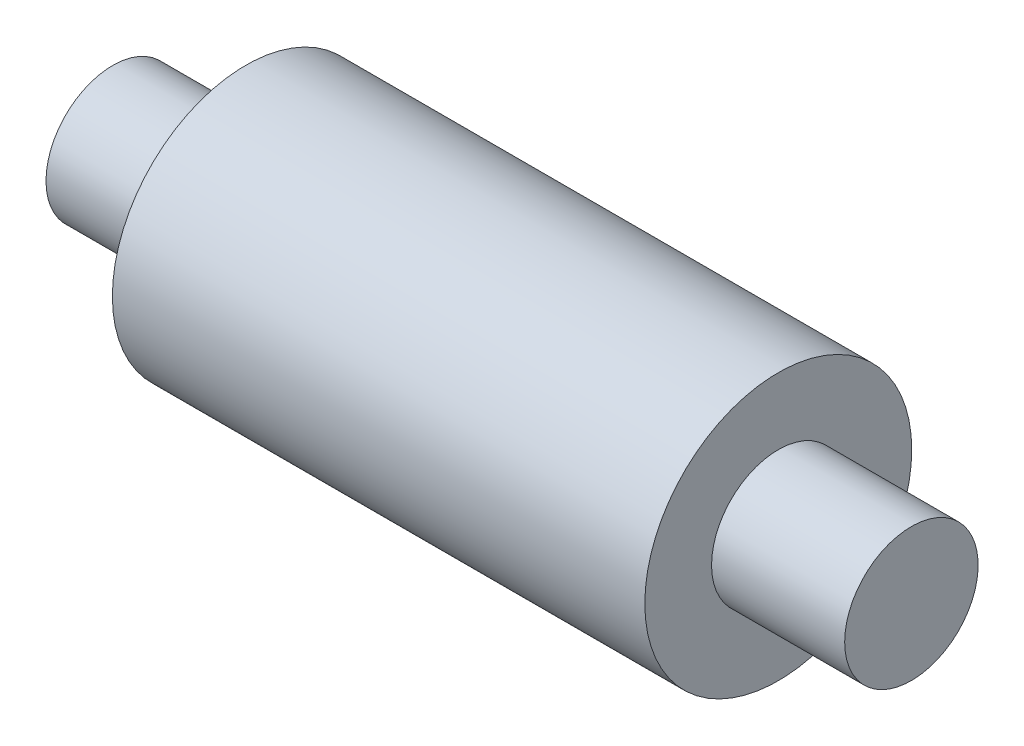
SolidWorks part; units mm, degrees
ref_plane "Front Plane" through (0, 0, 0) normal (0, 0, 1) x (1, 0, 0)
ref_plane "Top Plane" through (0, 0, 0) normal (0, 1, 0) x (1, 0, 0)
ref_plane "Right Plane" through (0, 0, 0) normal (1, 0, 0) x (0, 0, -1)
sketch "Sketch1" plane through (0, 0, 0) normal (0, 1, 0) x (1, 0, 0)
  line L0 (0, 4.7752) -> (0, 0)
  line L1 (0, 0) -> (9.525, 0)
  line L2 (9.525, 0) -> (9.525, -4.7752)
  line L3 (9.525, -4.7752) -> (47.625, -4.7752)
  line L5 (47.625, 0) -> (47.625, -4.7752)
  line L6 (57.15, 0) -> (47.625, 0)
  line L7 (57.15, 4.7752) -> (57.15, 0)
  line L8 (0, 4.7752) -> (57.15, 4.7752)
  dimension "D1" = 4.7752
  dimension "D2" = 9.525
  dimension "D3" = 4.7752
  dimension "D4" = 4.7752
  dimension "D5" = 4.7752
revolve "Revolve2" add sketch "Sketch1" angle 360 about L8
